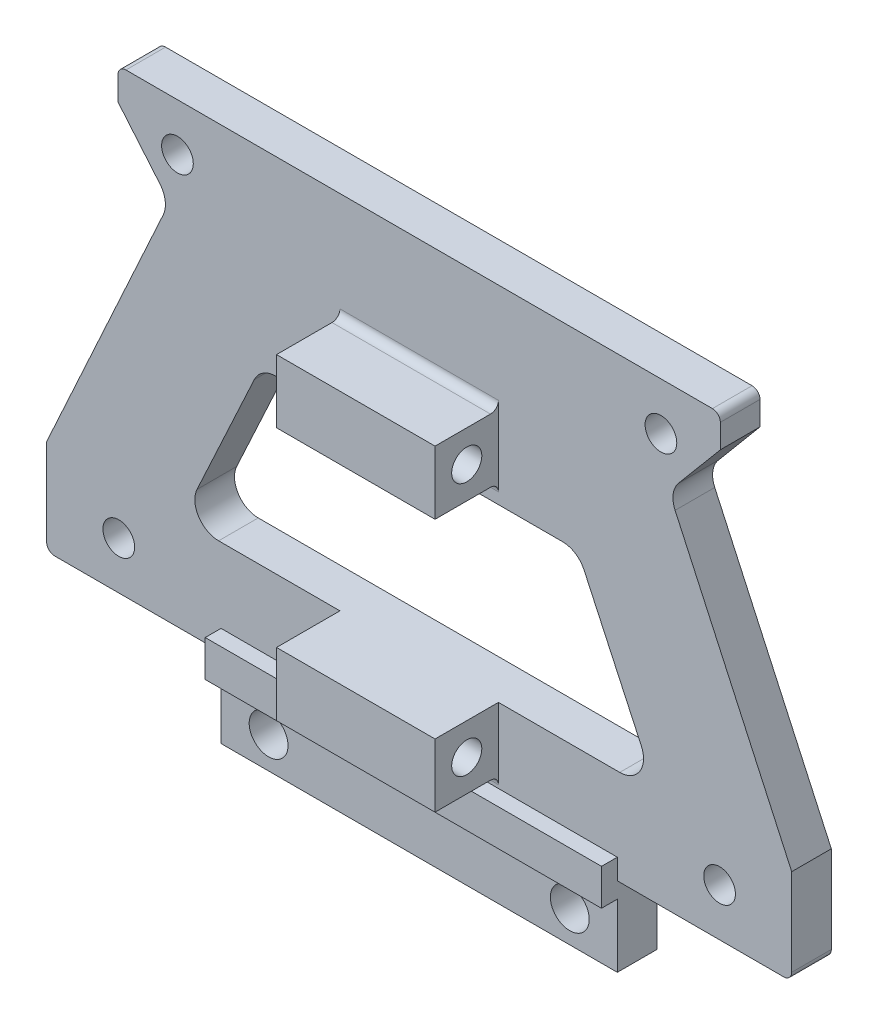
SolidWorks part; units mm, degrees
ref_plane "正面" through (0, 0, 0) normal (0, 0, 1) x (1, 0, 0)
ref_plane "平面" through (0, 0, 0) normal (0, 1, 0) x (1, 0, 0)
ref_plane "右側面" through (0, 0, 0) normal (1, 0, 0) x (0, 0, -1)
sketch "ｽｹｯﾁ1" plane through (0, 0, 0) normal (0, 0, 1) x (1, 0, 0)
  line L0 (0, 0) -> (0, -60.1493) construction
  line L1 (-34.0226, 8.3693) -> (37.2182, 8.3693) construction
  line L2 (-51.2483, -37.2307) -> (51.2307, -37.2307) construction
  line L24 (-47, -31.2307) -> (-47, -43.2307)
  line L25 (47, -31.2307) -> (47, -43.2307)
  line L26 (47, -43.2307) -> (-47, -43.2307)
  line L27 (38, 14.3693) -> (-38, 14.3693)
  line L28 (-20, -9.6307) -> (-30, -31.2307)
  line L29 (38, 10.3693) -> (31.5, 2.6193)
  line L30 (31.5, 2.6193) -> (47, -31.2307)
  line L31 (38, 14.3693) -> (38, 10.3693)
  line L32 (-38, 14.3693) -> (-38, 10.3693)
  line L33 (-38, 10.3693) -> (-31.5, 2.6193)
  line L34 (-31.5, 2.6193) -> (-47, -31.2307)
  line L35 (20, -9.6307) -> (30, -31.2307)
  line L36 (-20, -9.6307) -> (20, -9.6307)
  line L38 (-30, -31.2307) -> (30, -31.2307)
  circle A3 centre (-30.5, 8.3693) radius 2
  circle A4 centre (30.5, 8.3693) radius 2
  circle A5 centre (-37.9, -37.2307) radius 2
  circle A6 centre (37.9, -37.2307) radius 2
  dimension "D3" = 45.6
  dimension "D4" = 30.5
  dimension "D5" = 30.5
  dimension "D6" = 4
  dimension "D1" = 37.9
  dimension "D2" = 37.9
  dimension "D7" = 47
  dimension "D8" = 47
  dimension "D9" = 6
  dimension "D10" = 6
  dimension "D11" = 6
  dimension "D12" = 1
  dimension "D13" = 6
  dimension "D14" = 38
  dimension "D15" = 1
  dimension "D16" = 5.75
  dimension "D17" = 6
  dimension "D18" = 38
  dimension "D19" = 30
  dimension "D20" = 30
  dimension "D21" = 4
extrude "ﾎﾞｽ - 押し出し2" add sketch "ｽｹｯﾁ1" along normal blind 5
sketch "ｽｹｯﾁ3" plane through (0, 0, 5) normal (0, 0, 1) x (1, 0, 0)
  line L0 (0, 14.3693) -> (0, -42.7706) construction
  line L1 (10, 0.7693) -> (-10, 0.7693)
  line L2 (10, 0.7693) -> (10, -7.2307)
  line L3 (10, -7.2307) -> (-10, -7.2307)
  line L4 (-10, 0.7693) -> (-10, -7.2307)
  line L5 (38, 14.3693) -> (-38, 14.3693) construction
  line L6 (-30, -31.2307) -> (30, -31.2307) construction
  line L7 (10, -31.2307) -> (-10, -31.2307)
  line L8 (10, -31.2307) -> (10, -39.2307)
  line L9 (10, -39.2307) -> (-10, -39.2307)
  line L10 (-10, -31.2307) -> (-10, -39.2307)
  dimension "D1" = 10
  dimension "D2" = 8
  dimension "D3" = 8
  dimension "D4" = 40
  dimension "D5" = 20
extrude "ﾎﾞｽ - 押し出し3" add sketch "ｽｹｯﾁ3" along normal blind 8
sketch "ｽｹｯﾁ4" plane through (10, 0, 0) normal (1, 0, 0) x (0, 0, -1)
  line L0 (-9, 0.7693) -> (-9, -39.2307) construction
  line L1 (-13, 0.7693) -> (-5, 0.7693) construction
  line L2 (-13, -39.2307) -> (-5, -39.2307) construction
  line L3 (-5, -3.2307) -> (-13, -3.2307) construction
  line L4 (-5, -7.2307) -> (-5, 0.7693) construction
  line L5 (-13, -7.2307) -> (-13, 0.7693) construction
  line L6 (-5, -35.2307) -> (-13, -35.2307) construction
  line L7 (-5, -39.2307) -> (-5, -31.2307) construction
  line L8 (-13, -39.2307) -> (-13, -31.2307) construction
  circle A0 centre (-9, -3.2307) radius 1.9
  circle A1 centre (-9, -35.2307) radius 1.9
  dimension "D1" = 3.8
extrude "ｶｯﾄ - 押し出し1" cut sketch "ｽｹｯﾁ4" against normal through all
fillet "ﾌｨﾚｯﾄ1" radius 3 4 edges at (30, -31.2307, 2.5) (-30, -31.2307, 2.5) (20, -9.6307, 2.5) (-20, -9.6307, 2.5)
fillet "ﾌｨﾚｯﾄ2" radius 3 2 edges at (31.5, 2.6193, 2.5) (-31.5, 2.6193, 2.5)
sketch "ｽｹｯﾁ5" plane through (0, 0, 5) normal (0, 0, 1) x (1, 0, 0)
  line L5 (-47, -43.2307) -> (47, -43.2307) construction
  line L6 (-25, -43.2307) -> (25, -43.2307)
  line L7 (0, 62.4611) -> (0, -62.4611)
  line L8 (-25, -43.2307) -> (-25, -53.2307)
  line L13 (-25, -53.2307) -> (25, -53.2307)
  line L14 (25, -43.2307) -> (25, -53.2307)
  line L15 (-25, -43.2307) -> (25, -53.2307) construction
  line L16 (-25, -53.2307) -> (25, -43.2307) construction
  point P0 (0, -48.2307)
  point P11 (0, 0)
  line M28 (-47, -43.2307) -> (47, -43.2307)
  dimension "D1" = 50
  dimension "D2" = 10
extrude "ﾎﾞｽ - 押し出し4" add sketch "ｽｹｯﾁ5" against normal up to surface (5 mm away) contours L14 L6 L7 L13 | L8 L13 L7 M28 up to face at (-35.9, -37.2307, 0)
sketch "ｽｹｯﾁ6" plane through (0, 0, 5) normal (0, 0, 1) x (1, 0, 0)
  line L0 (0, -41.2307) -> (0, -55.8904) construction
  line L1 (-25, -53.2307) -> (25, -53.2307) construction
  line L2 (-25, -40.646) -> (25, -40.646)
  line L3 (-25, -40.646) -> (-25, -45.2307)
  line L4 (-25, -45.2307) -> (25, -45.2307)
  line L5 (25, -40.646) -> (25, -45.2307)
  line L6 (-25, -43.2307) -> (-25, -53.2307) construction
  line L7 (25, -43.2307) -> (25, -53.2307) construction
  dimension "D1" = 8
  dimension "D2" = 4.5847
extrude "ﾎﾞｽ - 押し出し5" add sketch "ｽｹｯﾁ6" along normal blind 2
sketch "ｽｹｯﾁ7" plane through (0, 0, 5) normal (0, 0, 1) x (1, 0, 0)
  line L0 (-25, -53.2307) -> (25, -53.2307) construction
  circle A0 centre (-19, -49.2307) radius 2.45
  circle A1 centre (19, -49.2307) radius 2.45
  dimension "D5" = 4.9
  dimension "D1" = 4
  dimension "D2" = 4
  dimension "D3" = 38
fillet "ﾌｨﾚｯﾄ3" radius 1 2 edges at (-38, 14.3693, 2.5) (38, 14.3693, 2.5)
fillet "ﾌｨﾚｯﾄ4" radius 1 2 edges at (47, -43.2307, 2.5) (-47, -43.2307, 2.5)
extrude "ｶｯﾄ - 押し出し2" cut sketch "ｽｹｯﾁ7" against normal blind 4 contours A1 | A0
fillet "ﾌｨﾚｯﾄ5" radius 1 2 edges at (0, 0.7693, 5) (0, -7.2307, 5)
fillet "ﾌｨﾚｯﾄ6" radius 1 1 edges at (0, -39.2307, 5)
